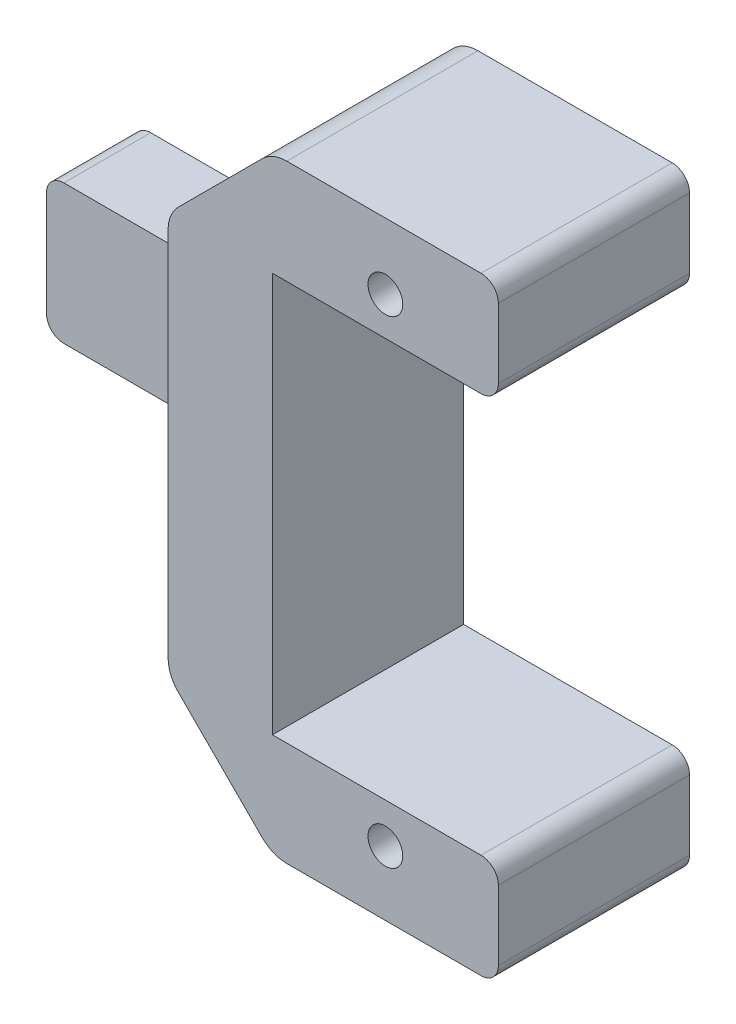
SolidWorks part; units mm, degrees
ref_plane "Front Plane" through (0, 0, 0) normal (0, 0, 1) x (1, 0, 0)
ref_plane "Top Plane" through (0, 0, 0) normal (0, 1, 0) x (1, 0, 0)
ref_plane "Right Plane" through (0, 0, 0) normal (1, 0, 0) x (0, 0, -1)
sketch "Sketch1" plane through (0, 0, 0) normal (0, 0, 1) x (1, 0, 0)
  line L0 (-54.3979, 39.098) -> (-66.3979, 39.098)
  line L1 (-72.3979, 33.098) -> (-72.3979, 25.598)
  line L2 (-72.3979, 25.598) -> (-84.3979, 25.598)
  line L3 (-85.3979, 24.598) -> (-85.3979, 18.598)
  line L4 (-84.3979, 17.598) -> (-72.3979, 17.598)
  line L5 (-66.3979, 4.098) -> (-54.3979, 4.098)
  line L6 (-72.3979, 10.098) -> (-72.3979, 17.598)
  line L7 (-53.3979, 5.098) -> (-53.3979, 9.098)
  line L8 (-54.3979, 10.098) -> (-66.3979, 10.098)
  line L9 (-66.3979, 10.098) -> (-66.3979, 33.098)
  line L10 (-66.3979, 33.098) -> (-54.3979, 33.098)
  line L11 (-53.3979, 34.098) -> (-53.3979, 38.098)
  line L12 (-72.3979, 39.098) -> (-66.3979, 39.098) construction
  line L13 (-72.3979, 39.098) -> (-72.3979, 33.098) construction
  line L14 (-66.3979, 39.098) -> (-72.3979, 33.098)
  line L15 (-72.3979, 10.098) -> (-66.3979, 4.098)
  arc A0 (-53.3979, 9.098) -> (-54.3979, 10.098) centre (-54.3979, 9.098) ccw
  arc A1 (-54.3979, 4.098) -> (-53.3979, 5.098) centre (-54.3979, 5.098) ccw
  arc A3 (-85.3979, 18.598) -> (-84.3979, 17.598) centre (-84.3979, 18.598) ccw
  arc A4 (-84.3979, 25.598) -> (-85.3979, 24.598) centre (-84.3979, 24.598) ccw
  arc A6 (-54.3979, 33.098) -> (-53.3979, 34.098) centre (-54.3979, 34.098) ccw
  arc A7 (-54.3979, 39.098) -> (-53.3979, 38.098) centre (-54.3979, 38.098) cw
  dimension "D5" = 1
  dimension "D4" = 8
extrude "Boss-Extrude1" add sketch "Sketch1" along normal blind 11
sketch "Sketch6" plane through (0, -0.304, 11) normal (0, 0, 1) x (1, 0, 0)
  circle A0 centre (-59.8979, 35.598) radius 1
  dimension "D1" = 2
extrude "Cut-Extrude7" cut sketch "Sketch6" against normal blind 11
sketch "Sketch7" plane through (0, 0.2048, 11) normal (0, 0, 1) x (1, 0, 0)
  circle A0 centre (-59.8979, 7.598) radius 1
  dimension "D1" = 2
extrude "Cut-Extrude8" cut sketch "Sketch7" against normal blind 11
sketch "Sketch8" plane through (0, 25.598, 0) normal (0, 1, 0) x (1, 0, 0)
  circle A0 centre (-78.8979, -2) radius 1
  dimension "D1" = 2
extrude "Cut-Extrude9" cut sketch "Sketch8" against normal blind 10 contours A0
sketch "Эскиз1" plane through (0, 0, 11) normal (0, 0, 1) x (1, 0, 0)
  line L0 (-72.3979, 17.598) -> (-72.3979, 25.598)
  line L1 (-72.3979, 25.598) -> (-84.3979, 25.598)
  line L2 (-85.3979, 24.598) -> (-85.3979, 18.598)
  line L3 (-84.3979, 17.598) -> (-72.3979, 17.598)
  arc A0 (-84.3979, 25.598) -> (-85.3979, 24.598) centre (-84.3979, 24.598) ccw
  arc A1 (-84.3979, 25.598) -> (-85.3979, 24.598) centre (-84.3979, 24.598) ccw construction
  arc A2 (-85.3979, 18.598) -> (-84.3979, 17.598) centre (-84.3979, 18.598) ccw
  point P15 (0, 0)
  point P17 (0, 0)
extrude "Вырез-Вытянуть1" cut sketch "Эскиз1" against normal blind 6
fillet "Скругление1" radius 2 4 edges at (-66.3979, 4.098, 5.5) (-72.3979, 10.098, 5.5) (-66.3979, 39.098, 5.5) (-72.3979, 33.098, 5.5)
